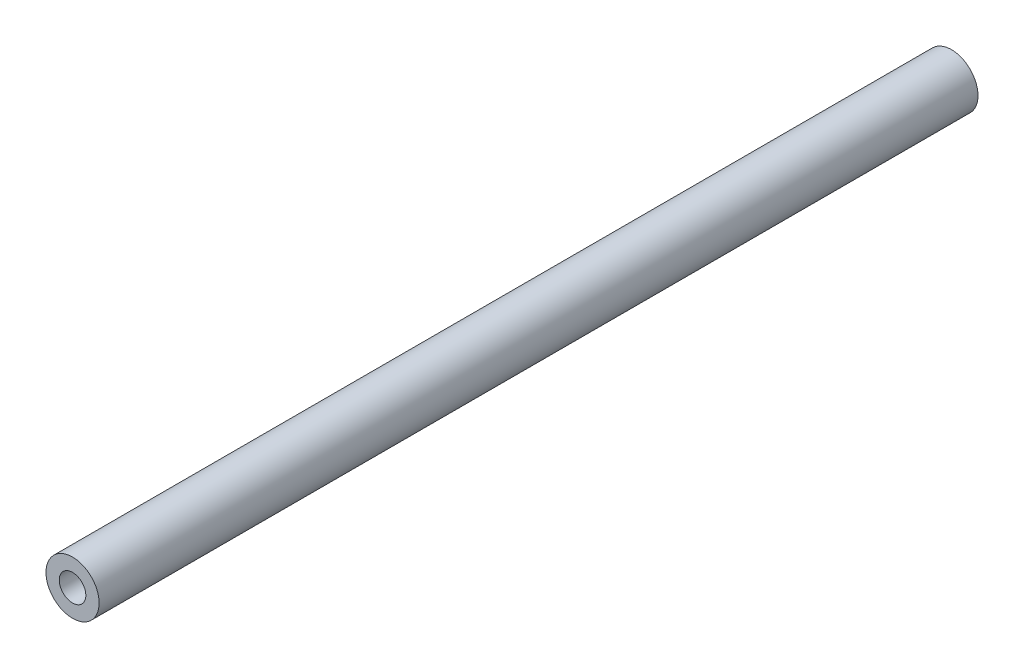
SolidWorks part; units mm, degrees
ref_plane "Front" through (0, 0, 0) normal (0, 0, 1) x (1, 0, 0)
ref_plane "Top" through (0, 0, 0) normal (0, 1, 0) x (1, 0, 0)
ref_plane "Right" through (0, 0, 0) normal (1, 0, 0) x (0, 0, -1)
sketch "Sketch1" plane through (0, 0, 0) normal (1, 0, 0) x (0, 0, -1)
  line L0 (-3810, 0) -> (3810, 0) construction
  line L1 (-3810, 6.35) -> (3810, 6.35)
  line L2 (-3810, 6.35) -> (-3810, 3.175)
  line L3 (-3810, 3.175) -> (3810, 3.175)
  line L4 (3810, 6.35) -> (3810, 3.175)
  point P4 (3797.3, 6.35)
  point P8 (0, 0)
  point P11 (-3797.3, 6.35)
  dimension "Length (Representative, 25ft)" = 7620
  dimension "ID" = 6.35
  dimension "OD" = 12.7
  dimension "D1" = 12.7
  dimension "D2" = 12.7
sketch "Sketch2" plane through (0, 0, 0) normal (1, 0, 0) x (0, 0, -1)
  line L0 (-3810, 6.35) -> (3810, 6.35) construction
  line L1 (3810, 6.35) -> (3810, 3.175) construction
  line L2 (-3810, 3.175) -> (3810, 3.175) construction
  line L3 (-3810, 6.35) -> (-3810, 3.175) construction
  line L4 (-3810, 6.35) -> (3810, 6.35)
  line L5 (3810, 6.35) -> (3810, 3.175)
  line L6 (-3810, 3.175) -> (3810, 3.175)
  line L7 (-3810, 6.35) -> (-3810, 3.175)
  line L8 (-3810, 0) -> (3810, 0) construction
  line L9 (-3810, 0) -> (3810, 0) construction
revolve "Revolve1" add sketch "Sketch2" angle 360 about L9
sketch "Sketch3" plane through (0, 0, 0) normal (0, 1, 0) x (1, 0, 0)
  line L1 (-631.1784, -3599.883) -> (493.1081, -3599.883)
  line L2 (-631.1784, -3599.883) -> (-631.1784, 4225.9367)
  line L3 (-631.1784, 4225.9367) -> (493.1081, 4225.9367)
  line L4 (493.1081, -3599.883) -> (493.1081, 4225.9367)
extrude "Cut-Extrude1" cut sketch "Sketch3" against normal through all both and the other way through all
equation "\"D1@Sketch1\"=\"OD@Sketch1\""
equation "\"D2@Sketch1\"=\"D1@Sketch1\""
